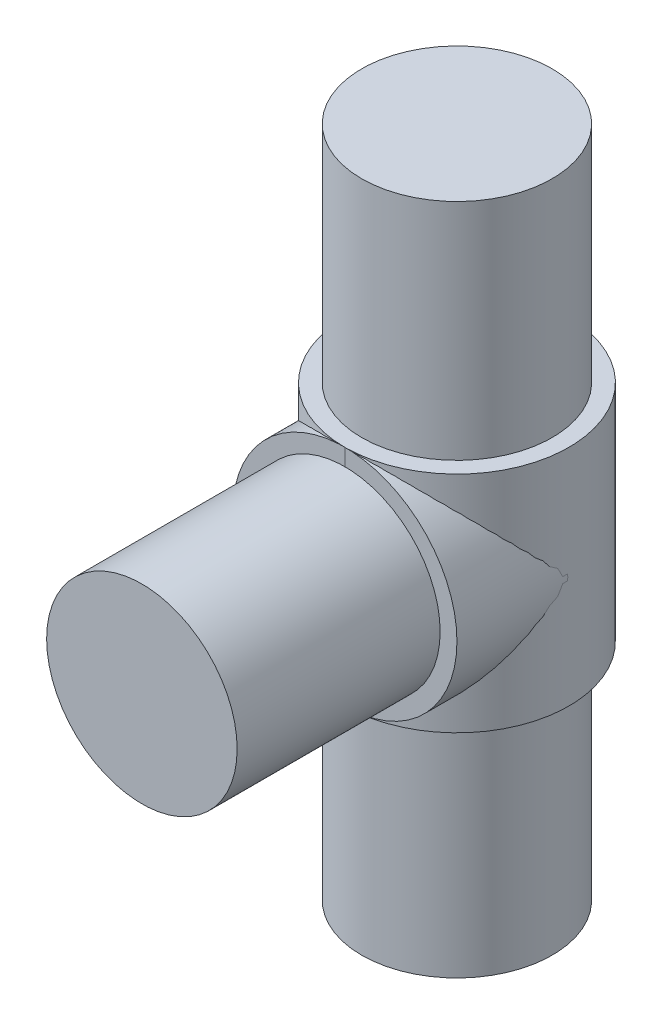
SolidWorks part; units mm, degrees
ref_plane "Front Plane" through (0, 0, 0) normal (0, 0, 1) x (1, 0, 0)
ref_plane "Top Plane" through (0, 0, 0) normal (0, 1, 0) x (1, 0, 0)
ref_plane "Right Plane" through (0, 0, 0) normal (1, 0, 0) x (0, 0, -1)
sketch "Sketch1" plane through (0, 0, 0) normal (0, 1, 0) x (1, 0, 0)
  circle A0 centre (-50.8892, 12.6093) radius 8.5
  dimension "D1" = 17
extrude "Boss-Extrude9" add sketch "Sketch1" along normal blind 60 contours A0
sketch "Sketch2" plane through (0, 0, 0) normal (0, 0, 1) x (1, 0, 0)
  line L0 (-42.3892, 60) -> (-59.3892, 60) construction
  line L1 (-42.3892, 0) -> (-42.3892, 60) construction
  circle A0 centre (-50.8892, 30) radius 8.5
  dimension "D1" = 17
  dimension "D2" = 30
  dimension "D3" = 8.5
extrude "Boss-Extrude10" add sketch "Sketch2" along normal blind 15.5 and the other way blind 13 separate body
sketch "Sketch3" plane through (0, 60, 0) normal (0, 1, 0) x (1, 0, 0)
  circle A0 centre (-50.8892, 12.6093) radius 10
  circle A1 centre (-50.8892, 12.6093) radius 8.5 construction
  dimension "D1" = 20
  dimension "D2" = 0
extrude "Boss-Extrude11" add sketch "Sketch3" along normal blind 0.0001 and the other way blind 38.5 separate body
other "Move Face1" face at (-50.8892, 60.0001, -2.6093) parameters "D1"=20.2
sketch "Sketch4" plane through (0, 0, 15.5) normal (0, 0, 1) x (1, 0, 0)
  circle A0 centre (-50.8892, 30) radius 10
  circle A1 centre (-50.8892, 30) radius 8.5 construction
  dimension "D1" = 20
  dimension "D2" = 0
extrude "Boss-Extrude12" add sketch "Sketch4" along normal blind 0.0001 and the other way blind 28 separate body
other "Move Face2" face at (-40.8892, 30, 15.5001) parameters "D1"=18.6
other "Move Face3" face at (-50.8892, 39.8001, -2.6093) parameters "D1"=0.1987
other "Move Face4" face at (-50.8892, 21.5, -2.6093) parameters "D1"=1.4939
other "Move Face5" face at (-40.8892, 30, -3.0999) parameters "D1"=0
other "Move Face6" face at (-40.8892, 30, -3.0999) parameters "D1"=0.6042
other "Move Face7" face at (-40.8892, 30, -2.4957) parameters "D1"=0.1159
